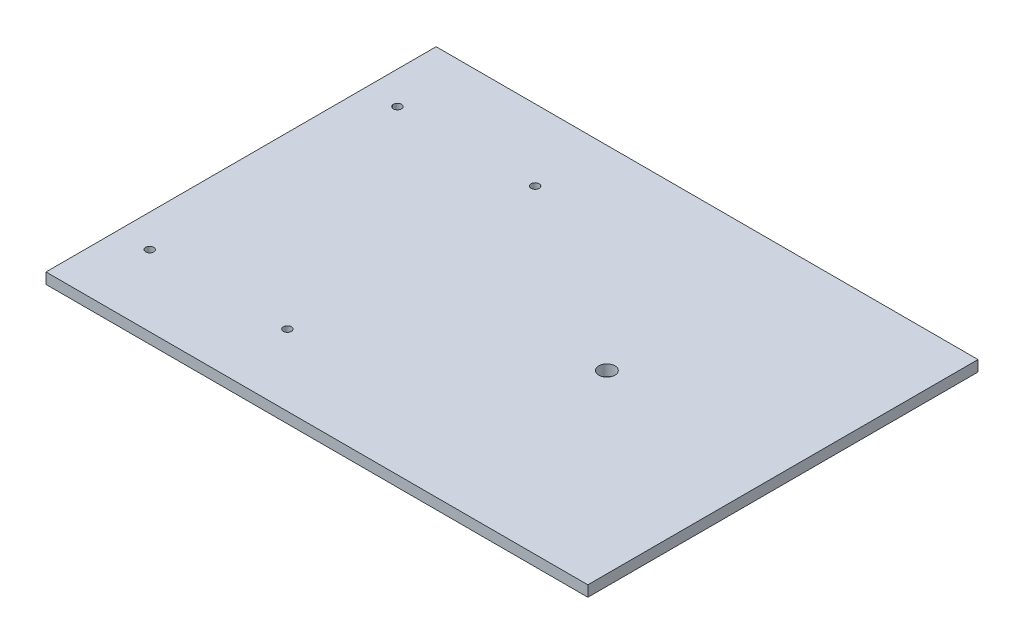
SolidWorks part; units mm, degrees
ref_plane "Front Plane" through (0, 0, 0) normal (0, 0, 1) x (1, 0, 0)
ref_plane "Top Plane" through (0, 0, 0) normal (0, 1, 0) x (1, 0, 0)
ref_plane "Right Plane" through (0, 0, 0) normal (1, 0, 0) x (0, 0, -1)
sketch "Sketch1" plane through (0, 0, 0) normal (0, 1, 0) x (1, 0, 0)
  line L1 (100, -72) -> (-100, -72)
  line L2 (100, -72) -> (100, 72)
  line L3 (100, 72) -> (-100, 72)
  line L4 (-100, -72) -> (-100, 72)
  line L5 (100, -72) -> (-100, 72) construction
  line L6 (100, 72) -> (-100, -72) construction
  point P0 (0, 0)
  dimension "D1" = 200
  dimension "D2" = 144
extrude "Boss-Extrude1" add sketch "Sketch1" along normal blind 4
sketch "Sketch2" plane through (0, 4, 0) normal (0, 1, 0) x (1, 0, 0)
  line L0 (-333.5342, 0) -> (93.1667, 0) construction
  line L1 (-100, 72) -> (-100, -72) construction
  line L2 (100, -72) -> (100, 72) construction
  circle A0 centre (35, 0) radius 3
  circle A1 centre (35, 0) radius 60 construction
  circle A2 centre (-88, 45.72) radius 1.4915
  circle A3 centre (-37.2, 45.72) radius 1.4915
  circle A4 centre (-37.2, -45.72) radius 1.4915
  circle A5 centre (-88, -45.72) radius 1.4915
  point P3 (-120.1838, 0)
  dimension "D1" = 6
  dimension "D3" = 2.9829
  dimension "D2" = 65
  dimension "D4" = 50.8
  dimension "D5" = 91.44
  dimension "D6" = 12
extrude "Cut-Extrude1" cut sketch "Sketch2" against normal through all
sketch3d "3DSketch1"
  point P0 (0, 2, 72)
sketch3d "3DSketch2"
  point P0 (35, 4, 0)
